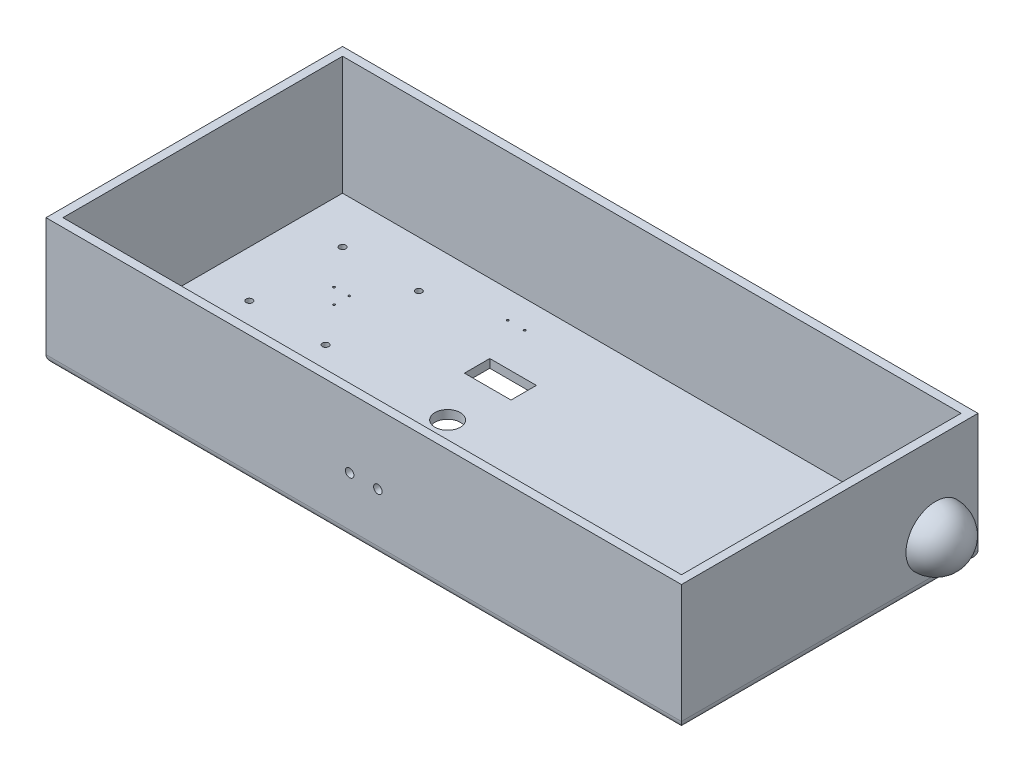
SolidWorks part; units mm, degrees
ref_plane "Front Plane" through (0, 0, 0) normal (0, 0, 1) x (1, 0, 0)
ref_plane "Top Plane" through (0, 0, 0) normal (0, 1, 0) x (1, 0, 0)
ref_plane "Right Plane" through (0, 0, 0) normal (1, 0, 0) x (0, 0, -1)
sketch "Sketch1" plane through (0, 0, 0) normal (0, 1, 0) x (1, 0, 0)
  line L1 (-75, 35) -> (75, 35)
  line L2 (-75, 35) -> (-75, -35)
  line L3 (-75, -35) -> (75, -35)
  line L4 (75, 35) -> (75, -35)
  line L5 (-75, 35) -> (75, -35) construction
  line L6 (-75, -35) -> (75, 35) construction
  point P0 (0, 0)
  dimension "D1" = 70
  dimension "D2" = 150
extrude "Boss-Extrude2" add sketch "Sketch1" along normal blind 30
shell "Shell1" thickness 2
sketch "Sketch3" plane through (0, 2, 0) normal (0, 1, 0) x (1, 0, 0)
  line L6 (-53, 47) -> (-53, 21.5034) construction
  line L7 (-47, 11) -> (-23, 11) construction
  line L8 (-73, 33) -> (-73, -33) construction
  line L9 (73, 33) -> (-73, 33) construction
  circle A0 centre (-62, 22) radius 0.75
  circle A1 centre (-44, 22) radius 0.75
  circle A2 centre (-44, 0) radius 0.75
  circle A3 centre (-62, 0) radius 0.75
  circle A4 centre (-54.795, 12.795) radius 0.25
  circle A5 centre (-51.205, 12.795) radius 0.25
  circle A6 centre (-51.205, 9.205) radius 0.25
  dimension "D5" = 1.5
  dimension "D6" = 0.5
  dimension "D7" = 0.5
  dimension "D1" = 11
  dimension "D2" = 22
  dimension "D3" = 18
  dimension "D4" = 11
  dimension "D8" = 0.5
  dimension "D9" = 3.59
  dimension "D10" = 3.59
  dimension "D11" = 1.795
  dimension "D12" = 1.795
  dimension "D13" = 1.795
  dimension "D14" = 1.795
extrude "Cut-Extrude2" cut sketch "Sketch3" against normal up to next
sketch "Sketch4" plane through (0, 0, 0) normal (0, -1, 0) x (1, 0, 0)
  line L0 (75, -35) -> (-75, -35) construction
  line L1 (-30, -24) -> (-21, -24)
  line L2 (-30, -24) -> (-30, -29)
  line L3 (-30, -29) -> (-21, -29)
  line L4 (-21, -24) -> (-21, -29)
  line L5 (-75, -35) -> (-75, 35) construction
  dimension "D1" = 5
  dimension "D2" = 9
  dimension "D3" = 6
  dimension "D4" = 45
extrude "Cut-Extrude3" cut sketch "Sketch4" against normal blind 1
sketch "Sketch5" plane through (0, 1, 0) normal (0, -1, 0) x (-1, 0, 0)
  line L0 (21, 24) -> (30, 24) construction
  line L1 (30, 24) -> (30, 29) construction
  circle A0 centre (27.5, 26.5) radius 0.25
  circle A1 centre (23.5, 26.5) radius 0.25
  dimension "D2" = 0.5
  dimension "D4" = 0.5
  dimension "D1" = 2.5
  dimension "D3" = 4
  dimension "D5" = 2.5
  dimension "D6" = 2.5
extrude "Cut-Extrude4" cut sketch "Sketch5" against normal up to next
sketch "Sketch8" plane through (0, 0, 0) normal (0, -1, 0) x (1, 0, 0)
  line L1 (-73, 33) -> (73, 33) construction
  line L2 (-75, -35) -> (-75, 35) construction
  line L3 (-21.8308, -10.6) -> (-10.8308, -10.6)
  line L4 (-21.8308, -10.6) -> (-21.8308, -16.5863)
  line L5 (-21.8308, -16.5863) -> (-10.8308, -16.5863)
  line L6 (-10.8308, -10.6) -> (-10.8308, -16.5863)
  line L7 (-21.8308, -10.6) -> (-10.8308, -16.5863) construction
  line L8 (-21.8308, -16.5863) -> (-10.8308, -10.6) construction
  circle A0 centre (-14.26, 0.94) radius 3
  circle A1 centre (-14.86, 12.48) radius 3
  point P8 (-16.3308, -13.5931)
  dimension "D1" = 6
  dimension "D2" = 20.52
  dimension "D3" = 6
  dimension "D5" = 60.14
  dimension "D6" = 60.74
  dimension "D4" = 11.54
  dimension "D7" = 11.54
  dimension "D8" = 11
extrude "Cut-Extrude7" cut sketch "Sketch8" against normal up to next
sketch "Sketch9" plane through (0, 0, 0) normal (0, -1, 0) x (1, 0, 0)
  line L4 (-20.3, -23.3) -> (-30.7, -23.3)
  line L5 (-30.7, -23.3) -> (-30.7, -29.7)
  line L6 (-30.7, -29.7) -> (-20.3, -29.7)
  line L7 (-20.3, -29.7) -> (-20.3, -23.3)
  line L8 (-30.5, -23.5) -> (-30.5, -29.5)
  line L9 (-20.5, -23.5) -> (-30.5, -23.5)
  line L10 (-20.5, -29.5) -> (-20.5, -23.5)
  line L11 (-30.5, -29.5) -> (-20.5, -29.5)
  line L12 (-30.5, -23.5) -> (-30.5, -29.5)
  line L13 (-20.5, -23.5) -> (-30.5, -23.5)
  line L14 (-20.5, -29.5) -> (-20.5, -23.5)
  line L15 (-30.5, -29.5) -> (-20.5, -29.5)
  dimension "D1" = 0.5
  dimension "D2" = 0.2
extrude "Boss-Extrude3" add sketch "Sketch9" along normal blind 3
sketch "Sketch10" plane through (0, -3, 0) normal (0, -1, 0) x (1, 0, 0)
  line L4 (-20.3, -29.7) -> (-20.3, -23.3)
  line L5 (-20.3, -23.3) -> (-30.7, -23.3)
  line L6 (-30.7, -23.3) -> (-30.7, -29.7)
  line L7 (-30.7, -29.7) -> (-20.3, -29.7)
  line L8 (-20.3, -29.7) -> (-20.3, -23.3)
  line L9 (-20.3, -23.3) -> (-30.7, -23.3)
  line L10 (-30.7, -23.3) -> (-30.7, -29.7)
  line L11 (-30.7, -29.7) -> (-20.3, -29.7)
  dimension "D1" = 0
extrude "Boss-Extrude4" add sketch "Sketch10" along normal blind 0.2
ref_plane "Plane1" through (50, 0, 0) normal (1, 0, 0) x (0, 0, -1)
fillet "Fillet1" radius 2 4 edges at (75, 0, 0) (0, 0, 35) (0, 0, -35) (-75, 0, 0)
fillet "Fillet3" radius 1.5 4 edges at (-30.7, 0, -26.5) (-25.5, 0, -23.3) (-20.3, 0, -26.5) (-25.5, 0, -29.7)
fillet "Fillet6" radius 0.5 4 edges at (-30.7, -3.2, -26.5) (-25.5, -3.2, -23.3) (-20.3, -3.2, -26.5) (-25.5, -3.2, -29.7)
sketch "Sketch15" plane through (0, 0, 0) normal (0, -1, 0) x (-1, 0, 0)
  line L0 (8.4771, -12.48) -> (-16.7894, -12.48) construction
  line L1 (8.4771, -1.062) -> (-16.7894, -1.062) construction
  line L2 (8.4771, 13.938) -> (-24.9053, 13.938) construction
  text T0 "DISTANCE"
  text T1 "TIMER"
  text T2 "Mode selector"
  dimension "D1" = 15
extrude "Cut-Extrude8" cut sketch "Sketch15" against normal blind 0.8
sketch "Sketch16" plane through (0, 0, 35) normal (0, 0, 1) x (1, 0, 0)
  line L0 (0, 2) -> (0, 30) construction
  line L1 (-75, 2) -> (75, 2) construction
  line L2 (-75, 30) -> (75, 30) construction
  circle A0 centre (3.33, 13.6583) radius 1
  circle A1 centre (-3.33, 13.6583) radius 1
  dimension "D1" = 2
  dimension "D2" = 2
  dimension "D4" = 6.66
  dimension "D3" = 3.33
extrude "Cut-Extrude9" cut sketch "Sketch16" against normal up to next
sketch "Sketch17" plane through (75, 0, 0) normal (1, 0, 0) x (0, 0, -1)
  line L0 (-35, 30) -> (35, 30) construction
  line L1 (35, 30) -> (35, 2) construction
  circle A0 centre (25, 10) radius 4.5
  dimension "D1" = 9
  dimension "D2" = 20
  dimension "D3" = 10
extrude "Cut-Extrude10" cut sketch "Sketch17" against normal blind 1
sketch "Sketch19" plane through (75, 0, 0) normal (1, 0, 0) x (0, 0, -1)
  line L0 (25, 10) -> (29.5, 10) construction
  circle A0 centre (25, 10) radius 4.5 construction
ref_plane "Plane2" through (0, 10, 0) normal (0, -1, 0) x (-1, 0, 0)
sketch "Sketch21" plane through (74, 0, 0) normal (1, 0, 0) x (0, 0, -1)
  line L2 (24.625, 10) -> (25.375, 10) construction
  line L3 (25, 10) -> (25, 11.3022) construction
  circle A0 centre (25.375, 10) radius 0.25
  circle A1 centre (24.375, 10) radius 0.25
  dimension "D1" = 0.5
  dimension "D2" = 0.5
  dimension "D3" = 1
extrude "Cut-Extrude11" cut sketch "Sketch21" against normal up to next
sketch "Sketch20" plane through (0, 10, 0) normal (0, -1, 0) x (-1, 0, 0)
  line L2 (-75, 25) -> (-75, 32)
  line L3 (-75, 25) -> (-82, 25)
  arc A1 (-75, 32) -> (-82, 25) centre (-75, 25) ccw
  dimension "D3" = 7
  dimension "D1" = 7
  dimension "D2" = 7
revolve "Revolve2" add sketch "Sketch20" angle 360 about L3
